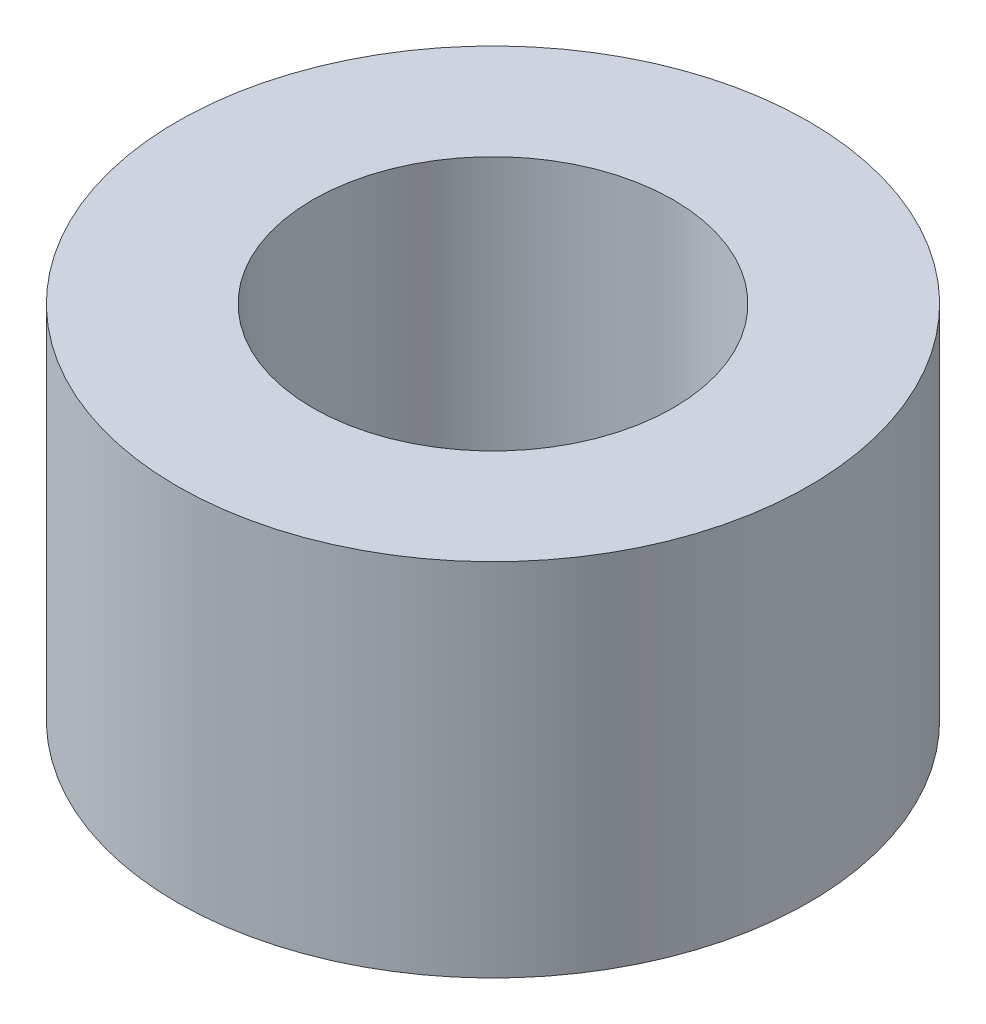
SolidWorks part; units mm, degrees
ref_plane "Front Plane" through (0, 0, 0) normal (0, 0, 1) x (1, 0, 0)
ref_plane "Top Plane" through (0, 0, 0) normal (0, 1, 0) x (1, 0, 0)
ref_plane "Right Plane" through (0, 0, 0) normal (1, 0, 0) x (0, 0, -1)
sketch "Sketch1" plane through (0, 0, 0) normal (0, 1, 0) x (1, 0, 0)
  circle A0 centre (0, 0) radius 4.7625
  circle A1 centre (0, 0) radius 5.5626
  dimension "D1" = 9.525
  dimension "D2" = 11.1252
extrude "Boss-Extrude1" add sketch "Sketch1" along normal blind 6.35 contours A1
sketch "Sketch2" plane through (0, 0, 0) normal (0, -1, 0) x (1, 0, 0)
  circle A0 centre (0, 0) radius 3.175
extrude "Cut-Extrude1" cut sketch "Sketch2" against normal blind 6.35
